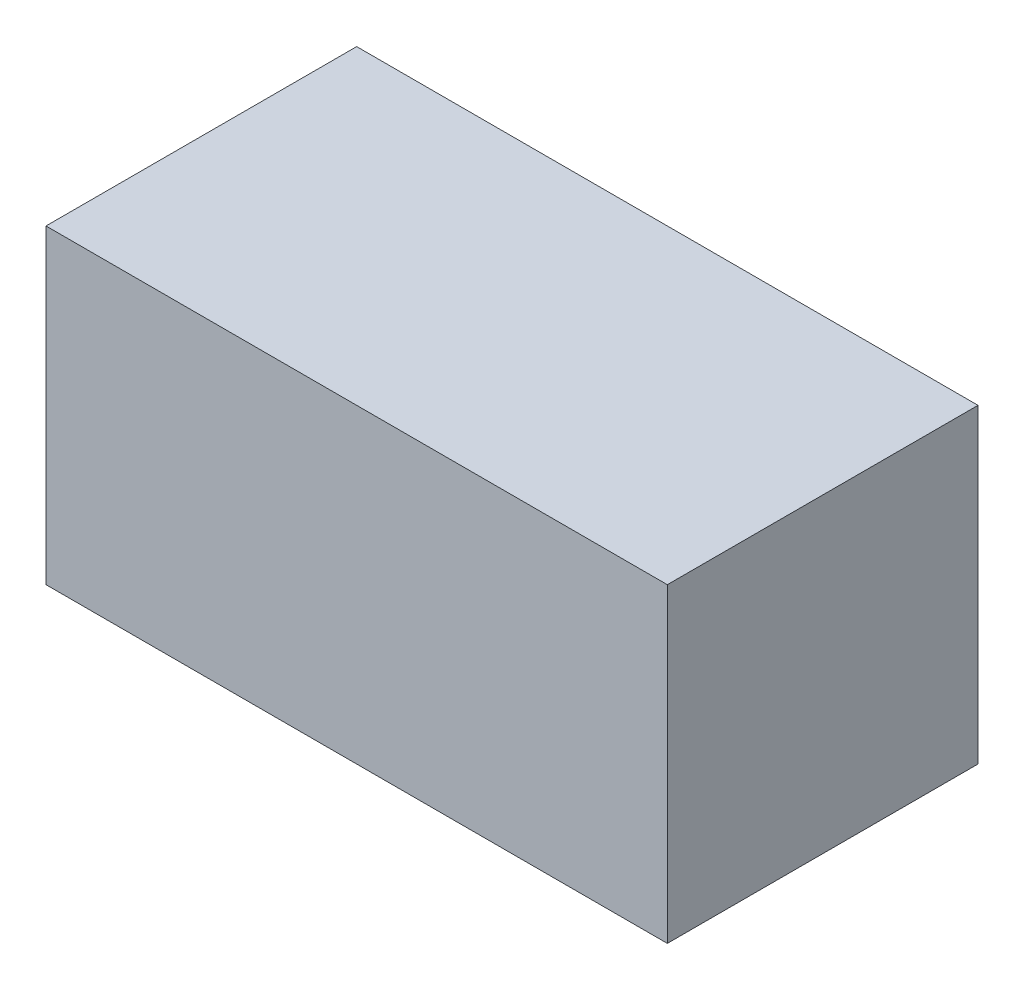
SolidWorks part; units mm, degrees
ref_plane "Front Plane" through (0, 0, 0) normal (0, 0, 1) x (1, 0, 0)
ref_plane "Top Plane" through (0, 0, 0) normal (0, 1, 0) x (1, 0, 0)
ref_plane "Right Plane" through (0, 0, 0) normal (1, 0, 0) x (0, 0, -1)
sketch "Sketch1" plane through (0, 0, 0) normal (0, 0, 1) x (1, 0, 0)
  line L1 (0, 0) -> (0.6, 0)
  line L2 (0, 0) -> (0, 0.3)
  line L3 (0, 0.3) -> (0.6, 0.3)
  line L4 (0.6, 0) -> (0.6, 0.3)
  dimension "D1" = 0.3
  dimension "D2" = 0.6
extrude "Boss-Extrude1" add sketch "Sketch1" along normal blind 0.3
